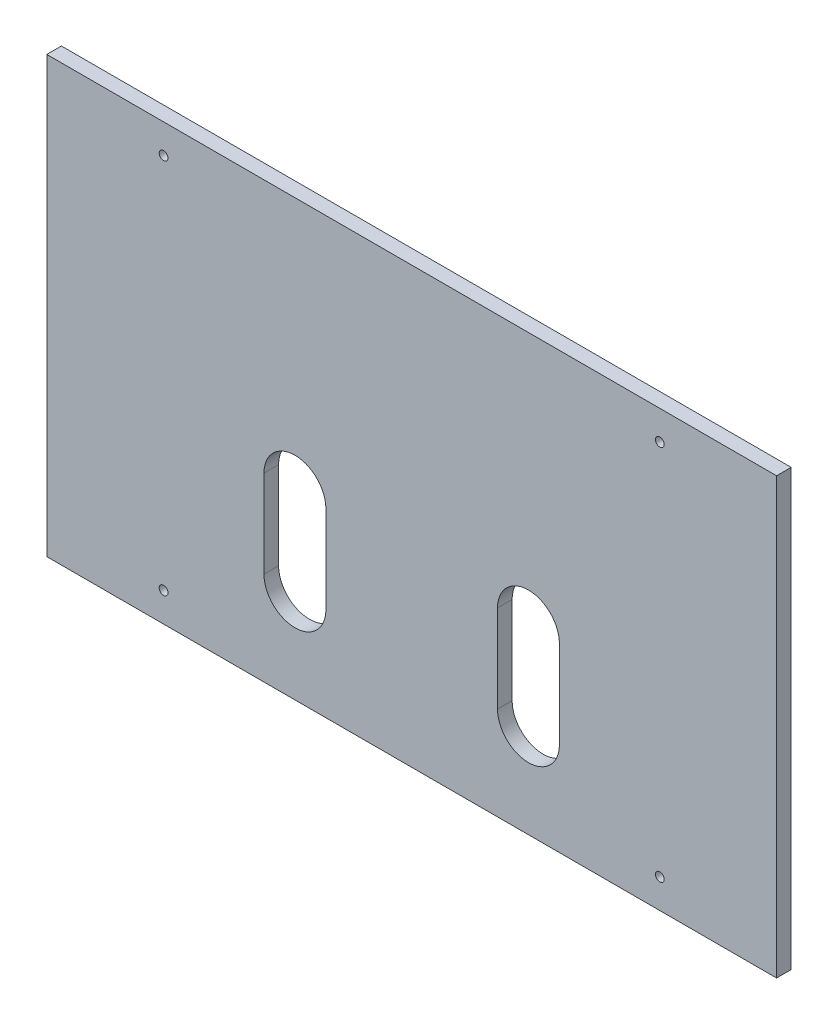
SolidWorks part; units mm, degrees
ref_plane "Plan de face" through (0, 0, 0) normal (0, 0, 1) x (1, 0, 0)
ref_plane "Plan de dessus" through (0, 0, 0) normal (0, 1, 0) x (1, 0, 0)
ref_plane "Plan de droite" through (0, 0, 0) normal (1, 0, 0) x (0, 0, -1)
sketch "Esquisse1" plane through (0, 0, 0) normal (0, 0, 1) x (1, 0, 0)
  line L1 (-125, 74.5) -> (125, 74.5)
  line L2 (-125, 74.5) -> (-125, -74.5)
  line L3 (-125, -74.5) -> (125, -74.5)
  line L4 (125, 74.5) -> (125, -74.5)
  line L5 (-125, 74.5) -> (125, -74.5) construction
  line L6 (-125, -74.5) -> (125, 74.5) construction
  point P0 (0, 0)
  dimension "D1" = 149
  dimension "D2" = 250
extrude "Boss.-Extru.1" add sketch "Esquisse1" along normal blind 5
sketch "Esquisse2" plane through (0, 0, 5) normal (0, 0, 1) x (1, 0, 0)
  line L0 (0, 0) -> (-59.8079, 0) construction
  line L1 (0, 0) -> (0, 59.4038) construction
  line L2 (125, 74.5) -> (-125, 74.5) construction
  line L3 (-125, 74.5) -> (-125, -74.5) construction
  circle A0 centre (-85, 64.5) radius 1.5
  circle A1 centre (-85, -64.5) radius 1.5
  circle A2 centre (85, -64.5) radius 1.5
  circle A3 centre (85, 64.5) radius 1.5
  dimension "D1" = 3
  dimension "D2" = 10
  dimension "D3" = 40
extrude "Enlèv. mat.-Extru.1" cut sketch "Esquisse2" against normal blind 5
sketch "Esquisse3" plane through (0, 0, 5) normal (0, 0, 1) x (1, 0, 0)
  line L0 (0, 0) -> (0, -74.5) construction
  line L1 (-125, -74.5) -> (125, -74.5) construction
  line L2 (-40, -12.5) -> (-40, -42.5) construction
  line L3 (-29.4, -12.5) -> (-29.4, -42.5)
  line L4 (-50.6, -12.5) -> (-50.6, -42.5)
  line L5 (40, -12.5) -> (40, -42.5) construction
  line L6 (29.4, -12.5) -> (29.4, -42.5)
  line L7 (50.6, -12.5) -> (50.6, -42.5)
  arc A0 (-29.4, -12.5) -> (-50.6, -12.5) centre (-40, -12.5) ccw
  arc A1 (-50.6, -42.5) -> (-29.4, -42.5) centre (-40, -42.5) ccw
  arc A2 (29.4, -12.5) -> (50.6, -12.5) centre (40, -12.5) cw
  arc A3 (50.6, -42.5) -> (29.4, -42.5) centre (40, -42.5) cw
  point P7 (-40, -27.5)
  point P14 (40, -27.5)
  dimension "D4" = 10.6
  dimension "D1" = 40
  dimension "D2" = 47
  dimension "D3" = 30
extrude "Enlèv. mat.-Extru.2" cut sketch "Esquisse3" against normal blind 5
